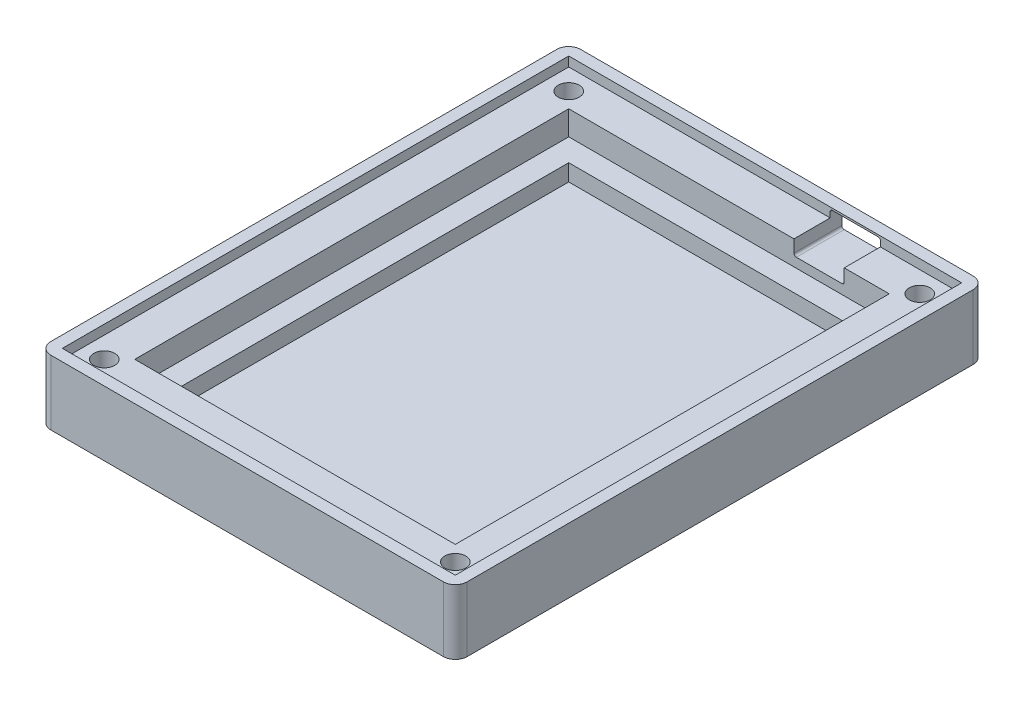
SolidWorks part; units mm, degrees
ref_plane "Front Plane" through (0, 0, 0) normal (0, 0, 1) x (1, 0, 0)
ref_plane "Top Plane" through (0, 0, 0) normal (0, 1, 0) x (1, 0, 0)
ref_plane "Right Plane" through (0, 0, 0) normal (1, 0, 0) x (0, 0, -1)
sketch "Sketch1" plane through (0, 0, 0) normal (0, 1, 0) x (1, 0, 0)
  line L1 (0, 0) -> (87.375, 0)
  line L2 (0, 0) -> (0, 111.187)
  line L3 (0, 111.187) -> (87.375, 111.187)
  line L4 (87.375, 0) -> (87.375, 111.187)
  dimension "D1" = 111.187
  dimension "D2" = 87.375
extrude "Frame-Block-Extrude" add sketch "Sketch1" along normal blind 13.6
sketch "Sketch2" plane through (0, 13.6, 0) normal (0, 1, 0) x (1, 0, 0)
  line L0 (87.375, 111.187) -> (0, 111.187) construction
  line L1 (2.45, 2.45) -> (84.925, 2.45)
  line L2 (2.45, 2.45) -> (2.45, 108.737)
  line L3 (2.45, 108.737) -> (84.925, 108.737)
  line L4 (84.925, 2.45) -> (84.925, 108.737)
  line L5 (0, 0) -> (87.375, 0) construction
  line L6 (0, 111.187) -> (0, 0) construction
  line L7 (87.375, 0) -> (87.375, 111.187) construction
  dimension "D1" = 2.45
  dimension "D2" = 2.45
  dimension "D3" = 2.45
  dimension "D4" = 2.45
extrude "Acrylic-Cut" cut sketch "Sketch2" against normal blind 2
sketch "Sketch3" plane through (0, 11.6, 0) normal (0, 1, 0) x (1, 0, 0)
  line L0 (84.925, 108.737) -> (2.45, 108.737) construction
  line L1 (10.05, 10.05) -> (77.325, 10.05)
  line L2 (10.05, 10.05) -> (10.05, 101.137)
  line L3 (10.05, 101.137) -> (77.325, 101.137)
  line L4 (77.325, 10.05) -> (77.325, 101.137)
  line L5 (2.45, 108.737) -> (2.45, 2.45) construction
  line L7 (2.45, 2.45) -> (84.925, 2.45) construction
  line L8 (84.925, 2.45) -> (84.925, 108.737) construction
  dimension "D1" = 7.6
  dimension "D2" = 7.6
  dimension "D3" = 7.6
  dimension "D4" = 7.6
extrude "PCB-Cut" cut sketch "Sketch3" against normal blind 5.1
sketch "Sketch4" plane through (0, 6.5, 0) normal (0, 1, 0) x (1, 0, 0)
  line L0 (77.325, 101.137) -> (10.05, 101.137) construction
  line L1 (14.75, 14.75) -> (72.625, 14.75)
  line L2 (14.75, 14.75) -> (14.75, 96.437)
  line L3 (14.75, 96.437) -> (72.625, 96.437)
  line L4 (72.625, 14.75) -> (72.625, 96.437)
  line L5 (10.05, 101.137) -> (10.05, 10.05) construction
  line L6 (77.325, 10.05) -> (77.325, 101.137) construction
  line L7 (10.05, 10.05) -> (77.325, 10.05) construction
  line L8 (84.925, 2.45) -> (84.925, 108.737) construction
  line L9 (87.375, 0) -> (87.375, 111.187) construction
  dimension "D1" = 4.7
  dimension "D2" = 4.7
  dimension "D3" = 4.7
  dimension "D4" = 4.7
  dimension "D5" = 2.45
extrude "PCB-Pins-Cut" cut sketch "Sketch4" against normal blind 3.5
sketch "Sketch5" plane through (0, 0, -111.187) normal (0, 0, -1) x (-1, 0, 0)
  line L0 (-87.375, 13.6) -> (-87.375, 0) construction
  line L1 (-67.875, 13.2) -> (-57.325, 13.2)
  line L2 (-67.875, 13.2) -> (-67.875, 8.5)
  line L3 (-67.875, 8.5) -> (-57.325, 8.5)
  line L4 (-57.325, 13.2) -> (-57.325, 8.5)
  line L6 (-87.375, 0) -> (0, 0) construction
  dimension "D1" = 10.55
  dimension "D2" = 4.7
  dimension "D3" = 19.5
  dimension "D4" = 8.5
extrude "Port-Cut" cut sketch "Sketch5" against normal blind 20
sketch "Sketch6" plane through (0, 11.6, 0) normal (0, 1, 0) x (1, 0, 0)
  line L0 (2.45, 108.737) -> (2.45, 2.45) construction
  line L1 (57.325, 108.737) -> (2.45, 108.737) construction
  line L4 (84.925, 2.45) -> (84.925, 108.737) construction
  line L5 (84.925, 108.737) -> (2.45, 108.737) construction
  line L6 (2.45, 2.45) -> (84.925, 2.45) construction
  line L7 (84.925, 2.45) -> (84.925, 108.737) construction
  circle A0 centre (6.85, 104.337) radius 2.2
  circle A1 centre (80.525, 104.337) radius 2.2
  circle A2 centre (80.525, 6.85) radius 2.2
  circle A3 centre (6.85, 6.85) radius 2.2
  dimension "D1" = 4.4
  dimension "D2" = 4.4
  dimension "D3" = 4.4
  dimension "D4" = 4.4
  dimension "D5" = 4.4
  dimension "D6" = 4.4
  dimension "D7" = 4.4
  dimension "D8" = 4.4
  dimension "D9" = 4.4
  dimension "D10" = 4.4
  dimension "D11" = 4.4
  dimension "D12" = 4.4
extrude "Heatset-Insert-Cuts" cut sketch "Sketch6" against normal blind 5
sketch "Sketch7" plane through (0, 6.6, 0) normal (0, 1, 0) x (1, 0, 0)
  circle A0 centre (80.525, 6.85) radius 1.5
  circle A1 centre (6.85, 6.85) radius 1.5
  circle A2 centre (6.85, 104.337) radius 1.5
  circle A3 centre (80.525, 104.337) radius 1.5
  dimension "D1" = 3
  dimension "D2" = 3
  dimension "D3" = 3
  dimension "D4" = 3
extrude "Screw-Cut" cut sketch "Sketch7" against normal blind 5
fillet "Corner-Fillet" radius 2.5 4 edges at (87.375, 6.8, -111.187) (0, 6.8, -111.187) (0, 6.8, 0) (87.375, 6.8, 0)
fillet "Port-Fillet" radius 0.5 4 edges at (67.875, 13.2, -109.962) (57.325, 13.2, -109.962) (57.325, 8.5, -106.162) (67.875, 8.5, -106.162)
sketch "Sketch9" plane through (0, 0, 0) normal (-1, 0, 0) x (0, 0, 1)
  line L0 (-108.687, 8) -> (-2.5, 8) construction
  line L1 (-108.687, 13.6) -> (-108.687, 0) construction
  line L2 (-2.5, 0) -> (-2.5, 13.6) construction
  line L3 (-108.687, 0) -> (-2.5, 0) construction
  line L4 (-108.687, 3.3427) -> (-2.5, 3.3427) construction
  line L5 (-105.8207, 13.6) -> (-105.8207, 0) construction
  line L6 (-108.687, 13.6) -> (-2.5, 13.6) construction
  text T0 "Presto's Macropad" font "Courier New" height in points 12
  text T1 "v1.0 // 4 - 2026" font "Century Gothic" height in points 6
  dimension "D1" = 8
extrude "Cut-Extrude1" cut sketch "Sketch9" against normal blind 0.5
